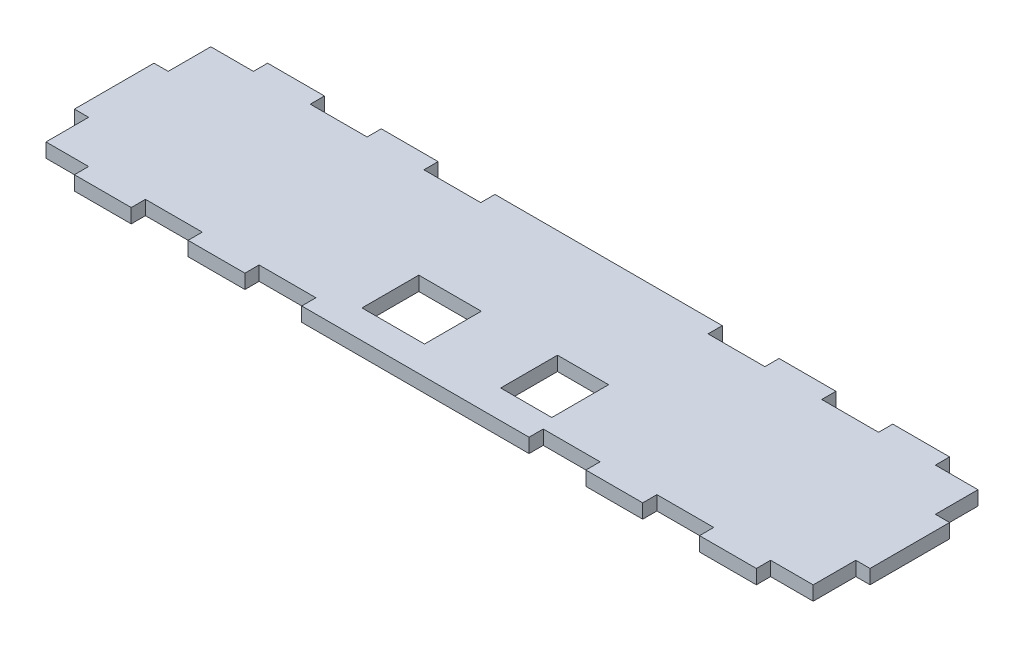
SolidWorks part; units mm, degrees
material "Acrylic (Medium-high impact)"
ref_plane "Front Plane" through (0, 0, 0) normal (0, 0, 1) x (1, 0, 0)
ref_plane "Top Plane" through (0, 0, 0) normal (0, 1, 0) x (1, 0, 0)
ref_plane "Right Plane" through (0, 0, 0) normal (1, 0, 0) x (0, 0, -1)
sketch "Sketch1" plane through (0, 0, 0) normal (0, 1, 0) x (1, 0, 0)
  line L1 (0, 0) -> (171.45, 0)
  line L2 (0, 0) -> (0, 36.83)
  line L3 (0, 36.83) -> (171.45, 36.83)
  line L4 (171.45, 0) -> (171.45, 36.83)
  dimension "D1" = 36.83
  dimension "D2" = 171.45
extrude "Boss-Extrude1" add sketch "Sketch1" along normal blind 3.175
sketch "Sketch2" plane through (0, 3.175, 0) normal (0, 1, 0) x (1, 0, 0)
  line L0 (85.725, 0) -> (85.725, -16.8439) construction
  line L1 (0, 0) -> (171.45, 0) construction
  line L2 (22.225, 0) -> (34.925, 0)
  line L3 (0, 0) -> (-3.175, 0)
  line L4 (0, 0) -> (0, -3.175)
  line L5 (0, -3.175) -> (-3.175, -3.175)
  line L6 (-3.175, 0) -> (-3.175, -3.175)
  line L7 (-3.175, 0) -> (9.525, 0)
  line L8 (-3.175, 0) -> (-3.175, -3.175)
  line L9 (-3.175, -3.175) -> (9.525, -3.175)
  line L10 (9.525, 0) -> (9.525, -3.175)
  line L11 (22.225, 0) -> (22.225, -3.175)
  line L12 (22.225, -3.175) -> (34.925, -3.175)
  line L13 (34.925, 0) -> (34.925, -3.175)
  line L14 (47.625, 0) -> (60.325, 0)
  line L15 (47.625, 0) -> (47.625, -3.175)
  line L16 (47.625, -3.175) -> (60.325, -3.175)
  line L17 (60.325, 0) -> (60.325, -3.175)
  line L18 (-3.175, -3.175) -> (174.625, -3.175)
  line L19 (85.725, -3.175) -> (85.725, 0)
  line L20 (174.625, 0) -> (-3.175, 0)
  line L21 (111.125, 0) -> (111.125, -3.175)
  line L22 (123.825, -3.175) -> (111.125, -3.175)
  line L23 (123.825, 0) -> (123.825, -3.175)
  line L24 (123.825, 0) -> (111.125, 0)
  line L25 (136.525, 0) -> (136.525, -3.175)
  line L26 (149.225, -3.175) -> (136.525, -3.175)
  line L27 (149.225, 0) -> (149.225, -3.175)
  line L28 (161.925, 0) -> (161.925, -3.175)
  line L29 (174.625, -3.175) -> (161.925, -3.175)
  line L30 (174.625, 0) -> (174.625, -3.175)
  line L31 (174.625, 0) -> (161.925, 0)
  line L32 (174.625, 0) -> (174.625, -3.175)
  line L33 (171.45, -3.175) -> (174.625, -3.175)
  line L34 (171.45, 0) -> (171.45, -3.175)
  line L35 (171.45, 0) -> (174.625, 0)
  line L36 (149.225, 0) -> (136.525, 0)
  line M3 (0, 0) -> (171.45, 0)
  dimension "D1" = 3.175
  dimension "D2" = 12.7
  dimension "D3" = 3
extrude "Boss-Extrude2" add sketch "Sketch2" against normal blind 3.175 contours L10 L18 L11 M3 | L13 L18 L15 M3 | L18 L19 L17 M3 | L21 L19 L18 M3 | L25 L23 L18 M3 | L28 L27 L18 M3 | L20
sketch "Sketch3" plane through (0, 3.175, 0) normal (0, 1, 0) x (1, 0, 0)
  line L0 (85.725, -3.175) -> (85.725, 3.175) construction
  line L1 (60.325, -3.175) -> (111.125, -3.175) construction
  line L2 (0, 3.175) -> (171.45, 3.175) construction
  line L3 (0, 36.83) -> (0, 0) construction
  line L4 (171.45, 0) -> (171.45, 36.83) construction
  line L6 (60.325, 0) -> (67.437, 0)
  line L7 (60.325, 0) -> (60.325, 25.654)
  line L8 (60.325, 25.654) -> (67.437, 25.654)
  line L9 (67.437, 0) -> (67.437, 25.654)
  line L10 (111.125, 0) -> (109.855, 0)
  line L11 (111.125, 0) -> (111.125, 29.21)
  line L12 (111.125, 29.21) -> (109.855, 29.21)
  line L13 (109.855, 0) -> (109.855, 29.21)
  line L14 (67.437, 3.175) -> (109.855, 3.175)
  line L15 (67.437, 3.175) -> (67.437, 15.875)
  line L16 (67.437, 15.875) -> (109.855, 15.875)
  line L17 (109.855, 3.175) -> (109.855, 15.875)
  dimension "D1" = 6.35
  dimension "D2" = 7.112
  dimension "D3" = 1.27
  dimension "D4" = 12.7
extrude "Cut-Extrude1" cut sketch "Sketch3" against normal blind 3.175 contours L14 L17 L16 L15
sketch "Sketch5" plane through (0, 3.175, 0) normal (0, 1, 0) x (1, 0, 0)
  line L0 (67.437, 3.175) -> (109.855, 3.175) construction
  line L1 (67.437, 15.875) -> (81.407, 15.875)
  line L2 (67.437, 15.875) -> (67.437, 3.175)
  line L3 (67.437, 3.175) -> (81.407, 3.175)
  line L4 (81.407, 15.875) -> (81.407, 3.175)
  line L5 (67.437, 15.875) -> (109.855, 15.875) construction
  line L6 (109.855, 3.175) -> (98.425, 3.175)
  line L7 (109.855, 3.175) -> (109.855, 15.875)
  line L8 (109.855, 15.875) -> (98.425, 15.875)
  line L9 (98.425, 3.175) -> (98.425, 15.875)
  line L11 (81.407, 15.875) -> (98.425, 15.875)
  line L12 (81.407, 15.875) -> (81.407, 3.175)
  line L13 (81.407, 3.175) -> (98.425, 3.175)
  line L14 (98.425, 15.875) -> (98.425, 3.175)
  line M26 (67.437, 15.875) -> (109.855, 15.875)
  line M28 (109.855, 3.175) -> (67.437, 3.175)
  dimension "D1" = 13.97
  dimension "D2" = 11.43
extrude "Boss-Extrude3" add sketch "Sketch5" against normal blind 3.175 contours L9 L4 M28 M26
sketch "Sketch6" plane through (0, 3.175, 0) normal (0, 1, 0) x (1, 0, 0)
  line L0 (0, 36.83) -> (0, 0) construction
  line L1 (9.525, -3.175) -> (-3.175, -3.175)
  line L2 (9.525, -3.175) -> (9.525, 9.525)
  line L3 (9.525, 9.525) -> (-3.175, 9.525)
  line L4 (-3.175, -3.175) -> (-3.175, 9.525)
  line L5 (161.925, -3.175) -> (174.625, -3.175)
  line L6 (161.925, -3.175) -> (161.925, 9.525)
  line L7 (161.925, 9.525) -> (174.625, 9.525)
  line L8 (174.625, -3.175) -> (174.625, 9.525)
  line L9 (0, 36.83) -> (-3.175, 36.83)
  line L10 (0, 36.83) -> (0, 40.005)
  line L11 (0, 40.005) -> (-3.175, 40.005)
  line L12 (-3.175, 36.83) -> (-3.175, 40.005)
  line L13 (171.45, 36.83) -> (174.625, 36.83)
  line L14 (171.45, 36.83) -> (171.45, 40.005)
  line L15 (171.45, 40.005) -> (174.625, 40.005)
  line L16 (174.625, 36.83) -> (174.625, 40.005)
  line L17 (174.625, 40.005) -> (161.925, 40.005)
  line L18 (174.625, 40.005) -> (174.625, 27.305)
  line L19 (174.625, 27.305) -> (161.925, 27.305)
  line L20 (161.925, 40.005) -> (161.925, 27.305)
  line L21 (-3.175, 40.005) -> (9.525, 40.005)
  line L22 (-3.175, 40.005) -> (-3.175, 27.305)
  line L23 (-3.175, 27.305) -> (9.525, 27.305)
  line L24 (9.525, 40.005) -> (9.525, 27.305)
  line L25 (-3.175, 27.305) -> (0, 27.305)
  line L26 (-3.175, 27.305) -> (-3.175, 9.525)
  line L27 (-3.175, 9.525) -> (0, 9.525)
  line L28 (0, 27.305) -> (0, 9.525)
  line L29 (171.45, 0) -> (171.45, 36.83) construction
  line L30 (174.625, 27.305) -> (171.45, 27.305)
  line L31 (174.625, 27.305) -> (174.625, 9.525)
  line L32 (174.625, 9.525) -> (171.45, 9.525)
  line L33 (171.45, 27.305) -> (171.45, 9.525)
  line M5 (0, 36.83) -> (0, 0)
  line M27 (171.45, 0) -> (171.45, 36.83)
  dimension "D1" = 12.7
  dimension "D2" = 12.7
  dimension "D3" = 12.7
  dimension "D4" = 3.175
  dimension "D5" = 3.175
  dimension "D6" = 12.7
  dimension "D7" = 12.7
extrude "Boss-Extrude4" add sketch "Sketch6" against normal blind 3.175 contours L31 L19 L7 M27 | L23 L26 L3 M5
ref_plane "Plane2" through (0, 0, -18.415) normal (0, 0, -1) x (-1, 0, 0)
mirror "Mirror1" about plane through (0, 0, -18.415) normal (0, 0, -1) of "Boss-Extrude2"
